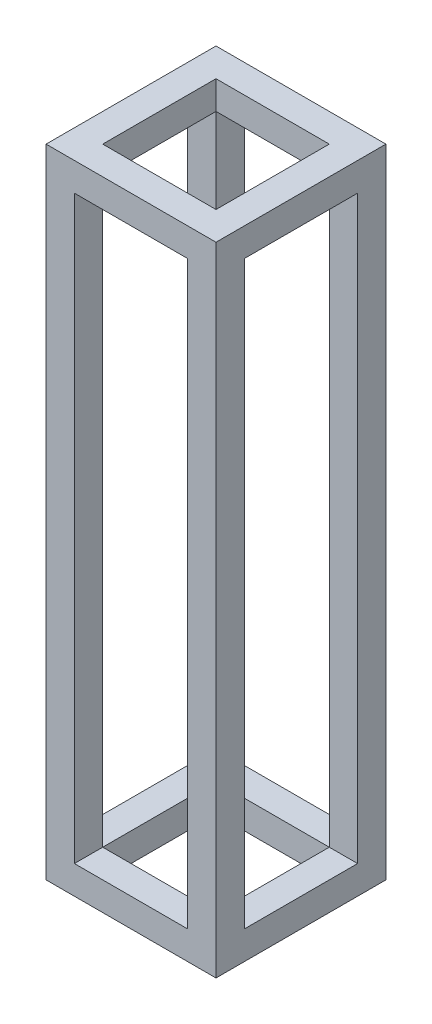
SolidWorks part; units mm, degrees
ref_plane "Front Plane" through (0, 0, 0) normal (0, 0, 1) x (1, 0, 0)
ref_plane "Top Plane" through (0, 0, 0) normal (0, 1, 0) x (1, 0, 0)
ref_plane "Right Plane" through (0, 0, 0) normal (1, 0, 0) x (0, 0, -1)
sketch "Sketch1" plane through (0, 0, 0) normal (0, 1, 0) x (1, 0, 0)
  line L1 (-60, 60) -> (60, 60)
  line L2 (-60, 60) -> (-60, -60)
  line L3 (-60, -60) -> (60, -60)
  line L4 (60, 60) -> (60, -60)
  line L5 (-60, 60) -> (60, -60) construction
  line L6 (-60, -60) -> (60, 60) construction
  line L7 (-40, 40) -> (40, 40)
  line L8 (-40, 40) -> (-40, -40)
  line L9 (-40, -40) -> (40, -40)
  line L10 (40, 40) -> (40, -40)
  line L11 (-40, 40) -> (40, -40) construction
  line L12 (-40, -40) -> (40, 40) construction
  point P0 (0, 0)
  point P6 (0, 0)
  dimension "D1" = 120
  dimension "D2" = 120
  dimension "D3" = 80
  dimension "D4" = 80
extrude "Boss-Extrude1" add sketch "Sketch1" along normal blind 20
ref_plane "Plane1" through (0, 450, 0) normal (0, 1, 0) x (1, 0, 0)
sketch "Sketch2" plane through (0, 450, 0) normal (0, 1, 0) x (1, 0, 0)
  line L1 (-60, 60) -> (-40, 60)
  line L2 (-60, 60) -> (-60, 40)
  line L3 (-60, 40) -> (-40, 40)
  line L4 (-40, 60) -> (-40, 40)
  line L5 (40, 40) -> (60, 40)
  line L6 (40, 40) -> (40, 60)
  line L7 (40, 60) -> (60, 60)
  line L8 (60, 40) -> (60, 60)
  line L9 (40, -40) -> (60, -40)
  line L10 (40, -40) -> (40, -60)
  line L11 (40, -60) -> (60, -60)
  line L12 (60, -40) -> (60, -60)
  line L13 (-40, -40) -> (-60, -40)
  line L14 (-40, -40) -> (-40, -60)
  line L15 (-40, -60) -> (-60, -60)
  line L16 (-60, -40) -> (-60, -60)
extrude "Boss-Extrude2" add sketch "Sketch2" against normal blind 450
sketch "Sketch4" plane through (0, 450, 0) normal (0, 1, 0) x (1, 0, 0)
  line L1 (-60, 60) -> (60, 60)
  line L2 (-60, 60) -> (-60, -60)
  line L3 (-60, -60) -> (60, -60)
  line L4 (60, 60) -> (60, -60)
  line L5 (-60, 60) -> (60, -60) construction
  line L6 (-60, -60) -> (60, 60) construction
  line L7 (-40, 40) -> (40, 40)
  line L8 (-40, 40) -> (-40, -40)
  line L9 (-40, -40) -> (40, -40)
  line L10 (40, 40) -> (40, -40)
  line L11 (-40, 40) -> (40, -40) construction
  line L12 (-40, -40) -> (40, 40) construction
  point P0 (0, 0)
  point P7 (0, 0)
extrude "Boss-Extrude3" add sketch "Sketch4" against normal blind 20
